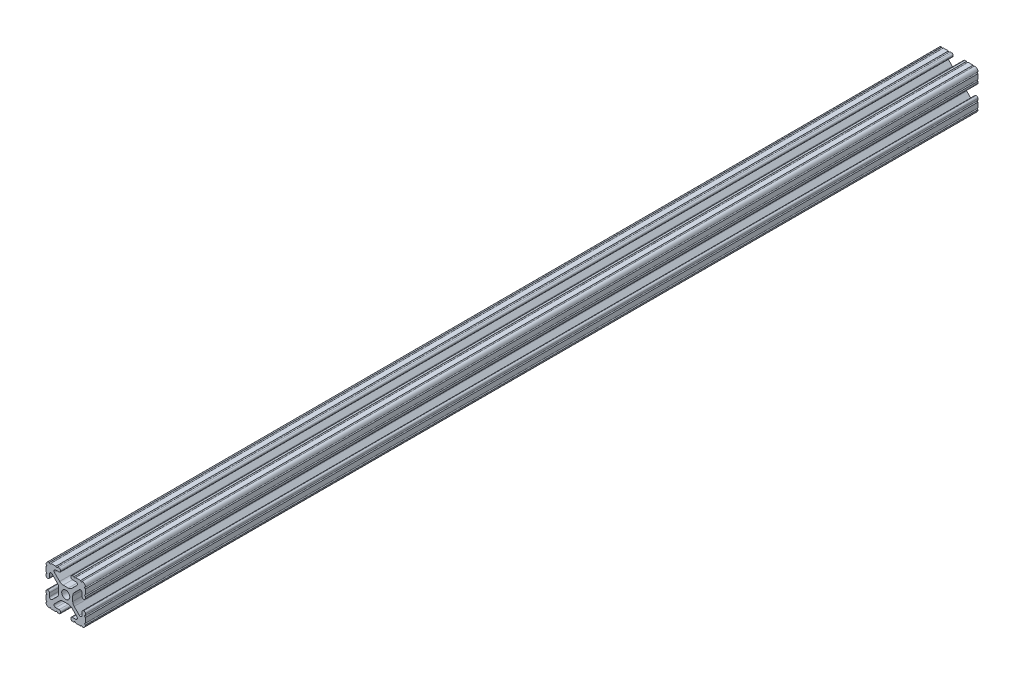
SolidWorks part; units mm, degrees
ref_plane "Front Plane" through (0, 0, 0) normal (0, 0, 1) x (1, 0, 0)
ref_plane "Top Plane" through (0, 0, 0) normal (0, 1, 0) x (1, 0, 0)
ref_plane "Right Plane" through (0, 0, 0) normal (1, 0, 0) x (0, 0, -1)
sketch "Sketch1" plane through (0, 0, 0) normal (0, 0, 1) x (1, 0, 0)
  line L88 (-7.1797, -8.6452) -> (-3.9523, -5.4237)
  line L89 (-1.7093, -4.4958) -> (1.7093, -4.4958)
  line L90 (3.9523, -5.4237) -> (7.1797, -8.6452)
  line L91 (6.4164, -10.4902) -> (4.2875, -10.4902)
  line L92 (3.2385, -11.5392) -> (3.2385, -11.651)
  line L93 (4.2875, -12.7) -> (5.3171, -12.7)
  line L94 (6.3331, -12.7) -> (9.5504, -12.7)
  line L95 (12.7, -9.5504) -> (12.7, -6.3331)
  line L96 (12.7, -5.3171) -> (12.7, -4.2875)
  line L97 (11.651, -3.2385) -> (11.5392, -3.2385)
  line L98 (10.4902, -4.2875) -> (10.4902, -6.4021)
  line L99 (8.7371, -7.1294) -> (5.441, -3.8408)
  line L100 (4.5085, -1.5932) -> (4.5085, 1.5932)
  line L101 (5.441, 3.8408) -> (8.7371, 7.1294)
  line L102 (10.4902, 6.4021) -> (10.4902, 4.2875)
  line L103 (11.5392, 3.2385) -> (11.651, 3.2385)
  line L104 (12.7, 4.2875) -> (12.7, 5.3171)
  line L105 (12.7, 6.3331) -> (12.7, 9.5504)
  line L106 (9.5504, 12.7) -> (6.3331, 12.7)
  line L107 (5.3171, 12.7) -> (4.2875, 12.7)
  line L108 (3.2385, 11.651) -> (3.2385, 11.5392)
  line L109 (4.2875, 10.4902) -> (6.4768, 10.4902)
  line L110 (7.207, 8.7244) -> (3.8983, 5.4232)
  line L111 (1.6558, 4.4958) -> (-1.6558, 4.4958)
  line L112 (-3.8983, 5.4232) -> (-7.207, 8.7244)
  line L113 (-6.4768, 10.4902) -> (-4.2875, 10.4902)
  line L114 (-3.2385, 11.5392) -> (-3.2385, 11.651)
  line L115 (-4.2875, 12.7) -> (-5.3171, 12.7)
  line L116 (-6.3331, 12.7) -> (-9.5504, 12.7)
  line L117 (-12.7, 9.5504) -> (-12.7, 6.3331)
  line L118 (-12.7, 5.3171) -> (-12.7, 4.2875)
  line L119 (-11.651, 3.2385) -> (-11.5392, 3.2385)
  line L120 (-10.4902, 4.2875) -> (-10.4902, 6.4021)
  line L121 (-8.7371, 7.1294) -> (-5.441, 3.8408)
  line L122 (-4.5085, 1.5932) -> (-4.5085, -1.5932)
  line L123 (-5.441, -3.8408) -> (-8.7371, -7.1294)
  line L124 (-10.4902, -6.4021) -> (-10.4902, -4.2875)
  line L125 (-11.5392, -3.2385) -> (-11.651, -3.2385)
  line L126 (-12.7, -4.2875) -> (-12.7, -5.3171)
  line L127 (-12.7, -6.3331) -> (-12.7, -9.5504)
  line L128 (-9.5504, -12.7) -> (-6.3331, -12.7)
  line L129 (-5.3171, -12.7) -> (-4.2875, -12.7)
  line L130 (-3.2385, -11.651) -> (-3.2385, -11.5392)
  line L131 (-4.2875, -10.4902) -> (-6.4164, -10.4902)
  circle A1 centre (0, 0) radius 2.6035
  arc A104 (-7.1797, -8.6452) -> (-6.4164, -10.4902) centre (-6.4164, -9.4098) ccw
  arc A105 (-1.7093, -4.4958) -> (-3.9523, -5.4237) centre (-1.7093, -7.6708) ccw
  arc A106 (3.9523, -5.4237) -> (1.7093, -4.4958) centre (1.7093, -7.6708) ccw
  arc A107 (6.4164, -10.4902) -> (7.1797, -8.6452) centre (6.4164, -9.4098) ccw
  arc A108 (4.2875, -10.4902) -> (3.2385, -11.5392) centre (4.2875, -11.5392) ccw
  arc A109 (3.2385, -11.651) -> (4.2875, -12.7) centre (4.2875, -11.651) ccw
  arc A110 (6.3331, -12.7) -> (5.3171, -12.7) centre (5.8251, -12.7) ccw
  arc A111 (10.5664, -12.6998) -> (9.5504, -12.7) centre (10.0584, -12.7) ccw
  arc A112 (10.5664, -12.6998) -> (12.6998, -10.5664) centre (10.5918, -10.5918) ccw
  arc A113 (12.7, -9.5504) -> (12.6998, -10.5664) centre (12.7, -10.0584) ccw
  arc A114 (12.7, -5.3171) -> (12.7, -6.3331) centre (12.7, -5.8251) ccw
  arc A115 (12.7, -4.2875) -> (11.651, -3.2385) centre (11.651, -4.2875) ccw
  arc A116 (11.5392, -3.2385) -> (10.4902, -4.2875) centre (11.5392, -4.2875) ccw
  arc A117 (8.7371, -7.1294) -> (10.4902, -6.4021) centre (9.4628, -6.4021) ccw
  arc A118 (4.5085, -1.5932) -> (5.441, -3.8408) centre (7.6835, -1.5932) ccw
  arc A119 (5.441, 3.8408) -> (4.5085, 1.5932) centre (7.6835, 1.5932) ccw
  arc A120 (10.4902, 6.4021) -> (8.7371, 7.1294) centre (9.4628, 6.4021) ccw
  arc A121 (10.4902, 4.2875) -> (11.5392, 3.2385) centre (11.5392, 4.2875) ccw
  arc A122 (11.651, 3.2385) -> (12.7, 4.2875) centre (11.651, 4.2875) ccw
  arc A123 (12.7, 6.3331) -> (12.7, 5.3171) centre (12.7, 5.8251) ccw
  arc A124 (12.6998, 10.5664) -> (12.7, 9.5504) centre (12.7, 10.0584) ccw
  arc A125 (12.6998, 10.5664) -> (10.5664, 12.6998) centre (10.5918, 10.5918) ccw
  arc A126 (9.5504, 12.7) -> (10.5664, 12.6998) centre (10.0584, 12.7) ccw
  arc A127 (5.3171, 12.7) -> (6.3331, 12.7) centre (5.8251, 12.7) ccw
  arc A128 (4.2875, 12.7) -> (3.2385, 11.651) centre (4.2875, 11.651) ccw
  arc A129 (3.2385, 11.5392) -> (4.2875, 10.4902) centre (4.2875, 11.5392) ccw
  arc A130 (7.207, 8.7244) -> (6.4768, 10.4902) centre (6.4768, 9.4563) ccw
  arc A131 (1.6558, 4.4958) -> (3.8983, 5.4232) centre (1.6558, 7.6708) ccw
  arc A132 (-3.8983, 5.4232) -> (-1.6558, 4.4958) centre (-1.6558, 7.6708) ccw
  arc A133 (-6.4768, 10.4902) -> (-7.207, 8.7244) centre (-6.4768, 9.4563) ccw
  arc A134 (-4.2875, 10.4902) -> (-3.2385, 11.5392) centre (-4.2875, 11.5392) ccw
  arc A135 (-3.2385, 11.651) -> (-4.2875, 12.7) centre (-4.2875, 11.651) ccw
  arc A136 (-6.3331, 12.7) -> (-5.3171, 12.7) centre (-5.8251, 12.7) ccw
  arc A137 (-10.5664, 12.6998) -> (-9.5504, 12.7) centre (-10.0584, 12.7) ccw
  arc A138 (-10.5664, 12.6998) -> (-12.6998, 10.5664) centre (-10.5918, 10.5918) ccw
  arc A139 (-12.7, 9.5504) -> (-12.6998, 10.5664) centre (-12.7, 10.0584) ccw
  arc A140 (-12.7, 5.3171) -> (-12.7, 6.3331) centre (-12.7, 5.8251) ccw
  arc A141 (-12.7, 4.2875) -> (-11.651, 3.2385) centre (-11.651, 4.2875) ccw
  arc A142 (-11.5392, 3.2385) -> (-10.4902, 4.2875) centre (-11.5392, 4.2875) ccw
  arc A143 (-8.7371, 7.1294) -> (-10.4902, 6.4021) centre (-9.4628, 6.4021) ccw
  arc A144 (-4.5085, 1.5932) -> (-5.441, 3.8408) centre (-7.6835, 1.5932) ccw
  arc A145 (-5.441, -3.8408) -> (-4.5085, -1.5932) centre (-7.6835, -1.5932) ccw
  arc A146 (-10.4902, -6.4021) -> (-8.7371, -7.1294) centre (-9.4628, -6.4021) ccw
  arc A147 (-10.4902, -4.2875) -> (-11.5392, -3.2385) centre (-11.5392, -4.2875) ccw
  arc A148 (-11.651, -3.2385) -> (-12.7, -4.2875) centre (-11.651, -4.2875) ccw
  arc A149 (-12.7, -6.3331) -> (-12.7, -5.3171) centre (-12.7, -5.8251) ccw
  arc A150 (-12.6998, -10.5664) -> (-12.7, -9.5504) centre (-12.7, -10.0584) ccw
  arc A151 (-12.6998, -10.5664) -> (-10.5664, -12.6998) centre (-10.5918, -10.5918) ccw
  arc A152 (-9.5504, -12.7) -> (-10.5664, -12.6998) centre (-10.0584, -12.7) ccw
  arc A153 (-5.3171, -12.7) -> (-6.3331, -12.7) centre (-5.8251, -12.7) ccw
  arc A154 (-4.2875, -12.7) -> (-3.2385, -11.651) centre (-4.2875, -11.651) ccw
  arc A155 (-3.2385, -11.5392) -> (-4.2875, -10.4902) centre (-4.2875, -11.5392) ccw
extrude "Boss-Extrude1" add sketch "Sketch1" along normal mid plane 574.7364
